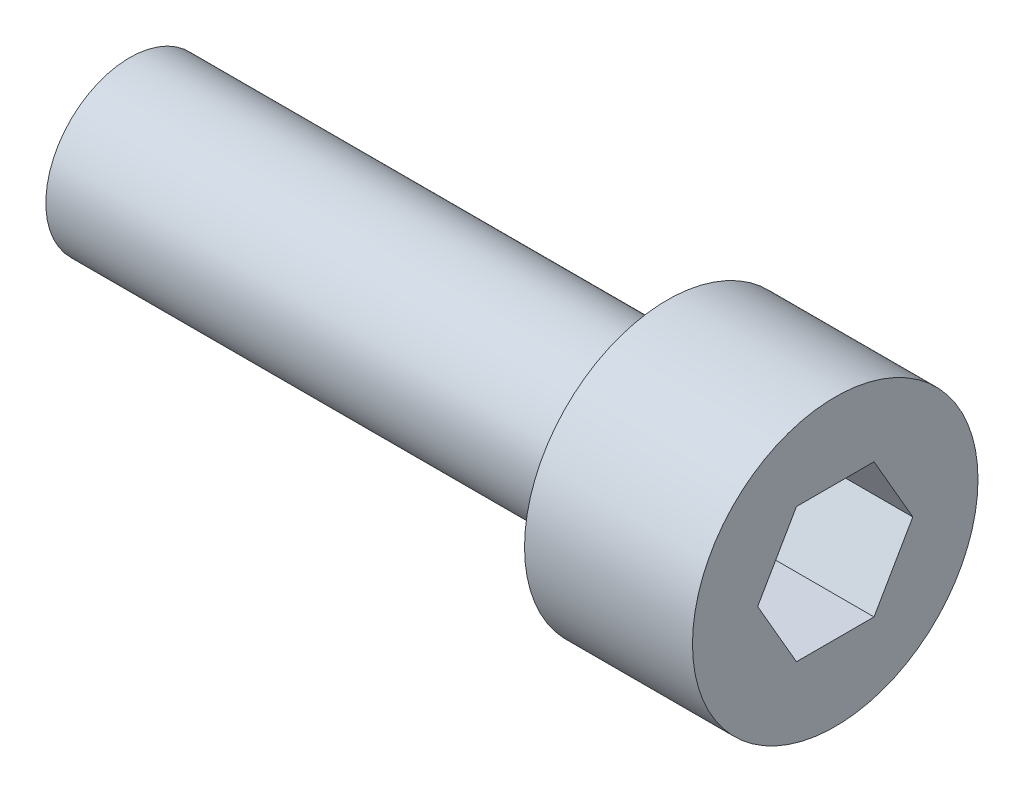
SolidWorks part; units mm, degrees
ref_plane "Plan de face" through (0, 0, 0) normal (0, 0, 1) x (1, 0, 0)
ref_plane "Plan de dessus" through (0, 0, 0) normal (0, 1, 0) x (1, 0, 0)
ref_plane "Plan de droite" through (0, 0, 0) normal (1, 0, 0) x (0, 0, -1)
sketch "Esquisse1" plane through (0, 0, 0) normal (1, 0, 0) x (0, 0, -1)
  circle A0 centre (0, 0) radius 2.5
  dimension "D1" = 5
extrude "Boss.-Extru.1" add sketch "Esquisse1" along normal blind 16
sketch "Esquisse2" plane through (16, 0, 0) normal (1, 0, 0) x (0, 0, -1)
  circle A0 centre (0, 0) radius 4.25
  dimension "D1" = 8.5
extrude "Boss.-Extru.2" add sketch "Esquisse2" along normal blind 5
sketch "Esquisse3" plane through (21, 0, 0) normal (1, 0, 0) x (0, 0, -1)
  line L1 (2.3094, 0) -> (1.1547, 2)
  line L2 (1.1547, 2) -> (-1.1547, 2)
  line L3 (-1.1547, 2) -> (-2.3094, 0)
  line L4 (-2.3094, 0) -> (-1.1547, -2)
  line L5 (-1.1547, -2) -> (1.1547, -2)
  line L6 (1.1547, -2) -> (2.3094, 0)
  circle A0 centre (0, 0) radius 2 construction
  dimension "D1" = 4
extrude "Enlèv. mat.-Extru.1" cut sketch "Esquisse3" against normal blind 3.5
